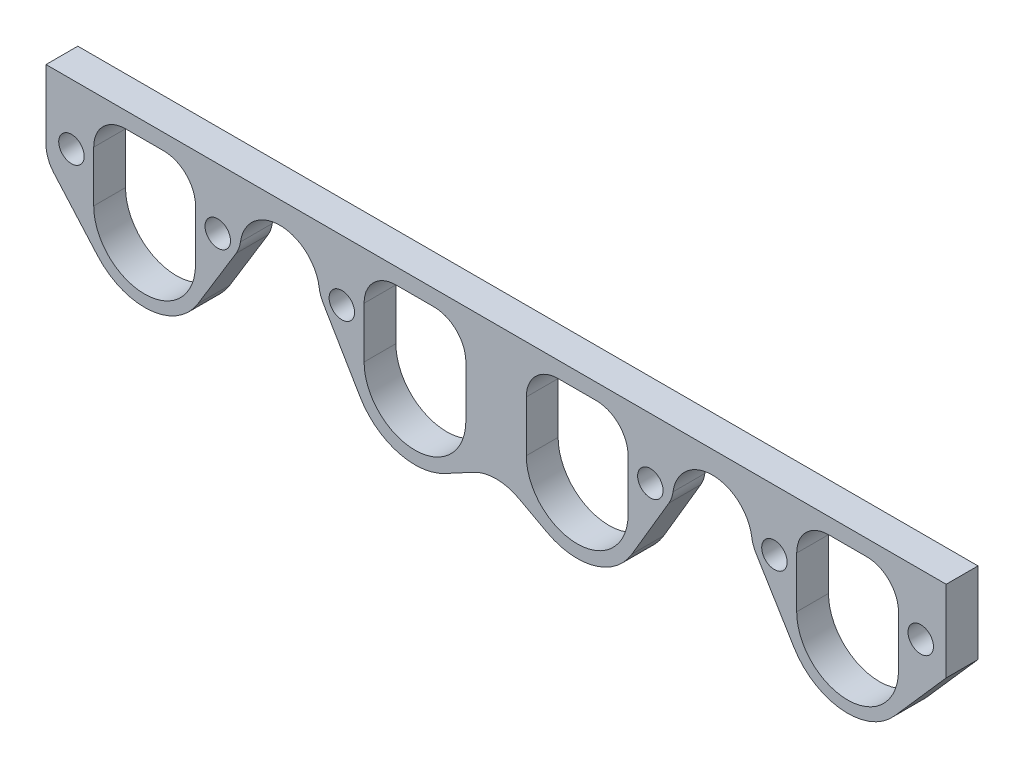
SolidWorks part; units mm, degrees
ref_plane "Alzado" through (0, 0, 0) normal (0, 0, 1) x (1, 0, 0)
ref_plane "Planta" through (0, 0, 0) normal (0, 1, 0) x (1, 0, 0)
ref_plane "Vista lateral" through (0, 0, 0) normal (1, 0, 0) x (0, 0, -1)
sketch "Croquis2" plane through (0, 0, 0) normal (0, 0, 1) x (1, 0, 0)
  line L1 (0, 0) -> (283, 0)
  line L2 (0, 0) -> (0, -51)
  line L3 (0, -51) -> (283, -51)
  line L4 (283, 0) -> (283, -51)
  dimension "D1" = 283
  dimension "D2" = 51
extrude "Saliente-Extruir1" add sketch "Croquis2" along normal blind 10
sketch "Croquis3" plane through (0, 0, 10) normal (0, 0, 1) x (1, 0, 0)
  line L0 (141.5, 58.5551) -> (141.5, -79.9446) construction
  line L1 (0, 0) -> (0, -51) construction
  line L2 (283, -51) -> (283, 0) construction
  line L3 (283, 0) -> (0, 0) construction
  line L8 (15, -31) -> (15, -5)
  line L9 (15, -5) -> (47, -5)
  line L10 (47, -5) -> (47, -31)
  line L11 (0, -51) -> (283, -51) construction
  line L12 (47.7807, -41.2153) -> (61, -19.5)
  line L13 (16.2483, -43.9743) -> (0, -25.5)
  line L14 (0, -25.5) -> (-5.4818, -47.9175)
  line L15 (-5.4818, -47.9175) -> (-5.4818, -72.9146)
  line L16 (-5.4818, -72.9146) -> (73.1844, -72.9146)
  line L19 (100, -31) -> (100, -5)
  line L20 (100, -5) -> (132, -5)
  line L21 (132, -5) -> (132, -31)
  line L22 (73.1844, -72.9146) -> (137.3504, -76.2203)
  line L23 (125.4687, -48.6166) -> (139.8523, -40.8856)
  line L26 (98.7723, -41.1591) -> (86, -19.5)
  line L27 (139.8523, -40.8856) -> (137.3504, -76.2203)
  line L28 (143.1477, -40.8856) -> (145.6496, -76.2203)
  line L29 (184.2277, -41.1591) -> (197, -19.5)
  line L30 (157.5313, -48.6166) -> (143.1477, -40.8856)
  line L31 (209.8156, -72.9146) -> (145.6496, -76.2203)
  line L32 (151, -5) -> (151, -31)
  line L33 (183, -5) -> (151, -5)
  line L34 (183, -31) -> (183, -5)
  line L35 (288.4818, -72.9146) -> (209.8156, -72.9146)
  line L36 (288.4818, -47.9175) -> (288.4818, -72.9146)
  line L37 (283, -25.5) -> (288.4818, -47.9175)
  line L38 (266.7517, -43.9743) -> (283, -25.5)
  line L39 (235.2193, -41.2153) -> (222, -19.5)
  line L40 (236, -5) -> (236, -31)
  line L41 (268, -5) -> (236, -5)
  line L42 (268, -31) -> (268, -5)
  circle A0 centre (8, -19) radius 4
  arc A2 (15, -31) -> (47, -31) centre (31, -31) ccw
  circle A3 centre (54, -19) radius 4
  arc A4 (86, -19.5) -> (61, -19.5) centre (73.5, -19.5) ccw
  arc A5 (16.2483, -43.9743) -> (47.7807, -41.2153) centre (31, -31) ccw
  circle A6 centre (93, -19) radius 4
  arc A7 (100, -31) -> (132, -31) centre (116, -31) ccw
  arc A8 (98.7723, -41.1591) -> (125.4687, -48.6166) centre (116, -31) ccw
  arc A9 (184.2277, -41.1591) -> (157.5313, -48.6166) centre (167, -31) cw
  arc A10 (183, -31) -> (151, -31) centre (167, -31) cw
  circle A11 centre (190, -19) radius 4
  arc A12 (266.7517, -43.9743) -> (235.2193, -41.2153) centre (252, -31) cw
  arc A13 (197, -19.5) -> (222, -19.5) centre (209.5, -19.5) cw
  circle A14 centre (229, -19) radius 4
  arc A15 (268, -31) -> (236, -31) centre (252, -31) cw
  circle A16 centre (275, -19) radius 4
  dimension "D1" = 8
  dimension "D4" = 32
  dimension "D2" = 20
  dimension "D7" = 8
  dimension "D9" = 19
  dimension "D10" = 7
  dimension "D11" = 8
  dimension "D12" = 25
  dimension "D13" = 19.5
  dimension "D16" = 8
  dimension "D17" = 19.5
  dimension "D19" = 16
  dimension "D20" = 26
  dimension "D3" = 19
  dimension "D5" = 5
  dimension "D6" = 7
  dimension "D8" = 32
  dimension "D14" = 19.5
  dimension "D15" = 7
  dimension "D18" = 32
  dimension "D21" = 26
extrude "Cortar-Extruir1" cut sketch "Croquis3" against normal blind 20
fillet "Redondeo1" radius 10 1 edges at (61, -19.5, 5)
fillet "Redondeo2" radius 10 6 edges at (132, -5, 5) (100, -5, 5) (15, -5, 5) (47, -5, 5) (0, -25.5, 5) (86, -19.5, 5)
ref_plane "Plano2" through (139.1362, -51, 10) normal (0.0706, 0.9975, 0) x (0.9975, -0.0706, 0)
sketch "Croquis6" plane through (0, 0, 10) normal (0, 0, 1) x (1, 0, 0)
  line L0 (141.5, 0) -> (141.5, -40)
  line L1 (283, 0) -> (0, 0) construction
  line L2 (139.8523, -40.8856) -> (141.5, -40)
  line L4 (143.1477, -40.8856) -> (141.5, -40)
  line L5 (139.8523, -40.8856) -> (135.448, -51.0162)
  line L6 (135.448, -51.0162) -> (145.0262, -51.8638)
  line L7 (145.0262, -51.8638) -> (144.8736, -43.964)
  line L8 (144.8736, -43.964) -> (143.1477, -40.8856)
  point P6 (139.8523, -40.8856)
  point P12 (0, 0)
  line M19 (139.8523, -40.8856) -> (139.1362, -51)
  line M20 (139.1362, -51) -> (143.8638, -51)
  line M21 (143.8638, -51) -> (143.1477, -40.8856)
  dimension "D1" = 40
extrude "Cortar-Extruir4" cut sketch "Croquis6" against normal blind 10 contours L4 L2 M21 M19 M20
fillet "Redondeo3" radius 15 1 edges at (141.5, -40, 5)
fillet "Redondeo4" radius 10 6 edges at (268, -5, 5) (236, -5, 5) (183, -5, 5) (151, -5, 5) (222, -19.5, 5) (197, -19.5, 5)
